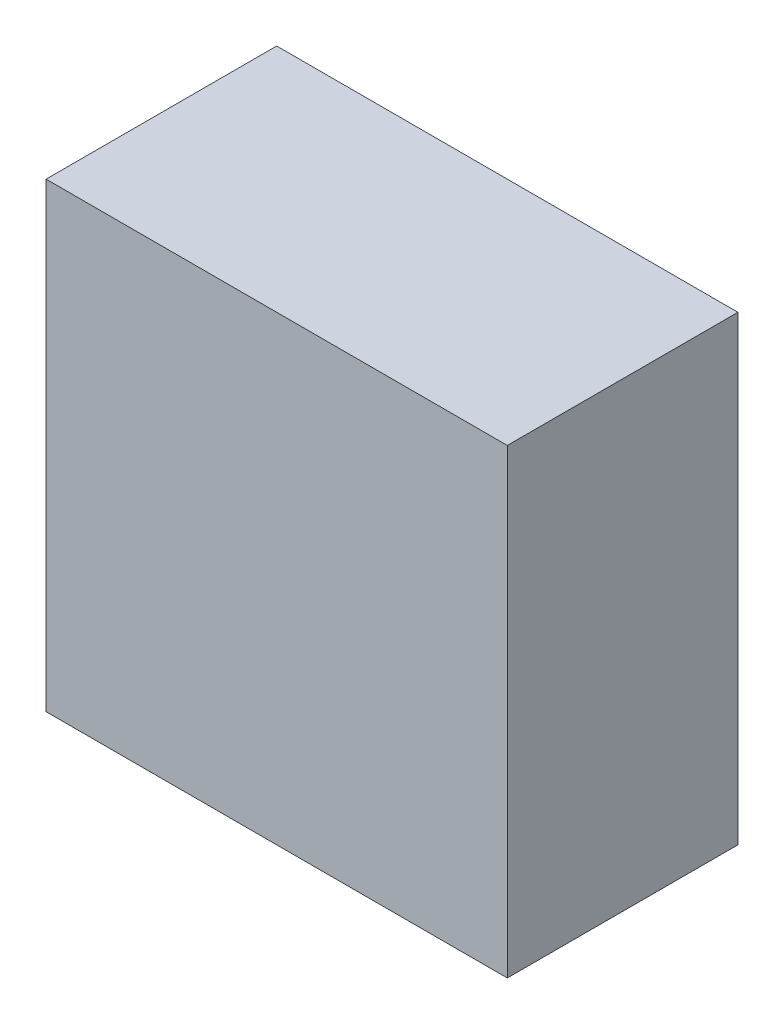
SolidWorks part; units mm, degrees
ref_plane "Front Plane" through (0, 0, 0) normal (0, 0, 1) x (1, 0, 0)
ref_plane "Top Plane" through (0, 0, 0) normal (0, 1, 0) x (1, 0, 0)
ref_plane "Right Plane" through (0, 0, 0) normal (1, 0, 0) x (0, 0, -1)
sketch "Sketch1" plane through (0, 0, 0) normal (0, 1, 0) x (1, 0, 0)
  line L0 (0, 0) -> (12.7, 0)
  line L1 (12.7, 0) -> (12.7, 6.35)
  line L2 (12.7, 6.35) -> (0, 6.35)
  line L3 (0, 6.35) -> (0, 0)
  dimension "D1" = 12.7
  dimension "D2" = 6.35
extrude "Boss-Extrude1" add sketch "Sketch1" along normal blind 12.7
